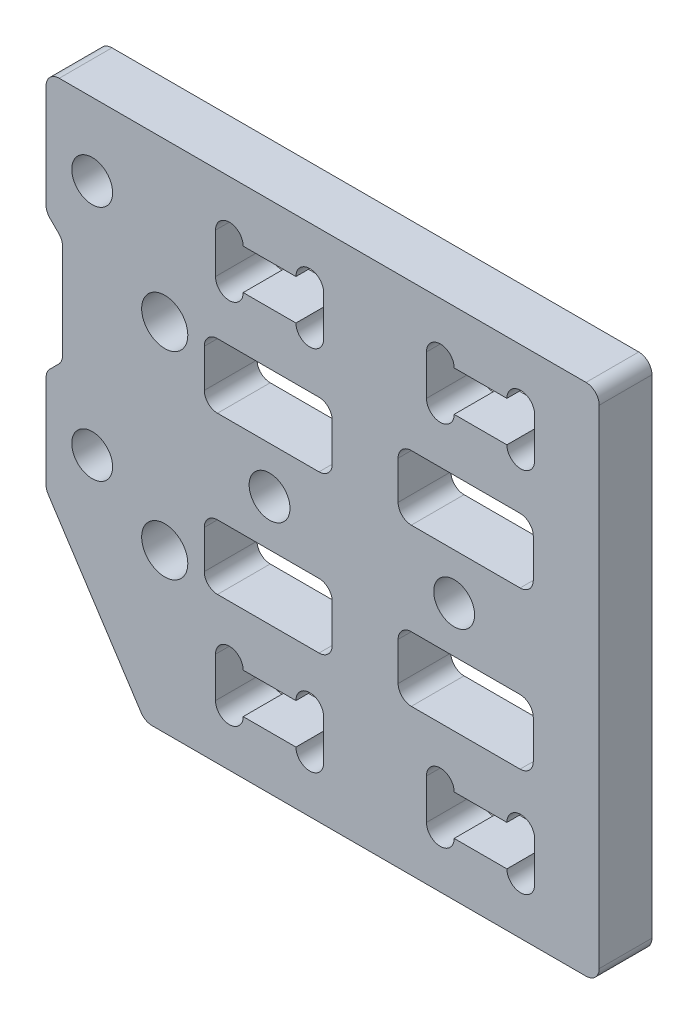
SolidWorks part; units mm, degrees
material "Thornel Mat VMA"
ref_plane "前视基准面" through (0, 0, 0) normal (0, 0, 1) x (1, 0, 0)
ref_plane "上视基准面" through (0, 0, 0) normal (0, 1, 0) x (1, 0, 0)
ref_plane "右视基准面" through (0, 0, 0) normal (1, 0, 0) x (0, 0, -1)
sketch "草图1" plane through (0, 0, 0) normal (0, 0, 1) x (1, 0, 0)
  line L0 (-24.725, 13.925) -> (34.2998, 13.925) construction
  line L1 (17.225, -19.5) -> (-17.225, -19.5)
  line L2 (17.225, -19.5) -> (17.225, 19.5)
  line L3 (17.225, 19.5) -> (-14.225, 19.5)
  line L4 (-17.225, -19.5) -> (-17.225, 19.5) construction
  line L5 (17.225, -19.5) -> (-17.225, 19.5) construction
  line L6 (17.225, 19.5) -> (-17.225, -19.5) construction
  line L7 (0, 0) -> (25.8004, 0) construction
  line L8 (-24.725, -13.925) -> (34.2998, -13.925) construction
  line L9 (-24.725, 19.5) -> (-24.725, 10.25)
  line L10 (-3.675, 12.4) -> (-11.875, 12.4)
  line L11 (-3.675, 12.4) -> (-3.675, 15.45)
  line L12 (-3.675, 15.45) -> (-11.875, 15.45)
  line L13 (-11.875, 12.4) -> (-11.875, 15.45)
  line L14 (-3.675, 12.4) -> (-11.875, 15.45) construction
  line L15 (-3.675, 15.45) -> (-11.875, 12.4) construction
  line L16 (12.325, 12.4) -> (4.125, 12.4)
  line L17 (12.325, 12.4) -> (12.325, 15.45)
  line L18 (12.325, 15.45) -> (4.125, 15.45)
  line L19 (4.125, 12.4) -> (4.125, 15.45)
  line L20 (12.325, 12.4) -> (4.125, 15.45) construction
  line L21 (12.325, 15.45) -> (4.125, 12.4) construction
  line L23 (-21.225, -4) -> (-21.225, 14) construction
  line L24 (4.125, -15.45) -> (12.325, -15.45)
  line L25 (4.125, -15.45) -> (4.125, -12.4)
  line L26 (4.125, -12.4) -> (12.325, -12.4)
  line L27 (12.325, -15.45) -> (12.325, -12.4)
  line L28 (4.125, -15.45) -> (12.325, -12.4) construction
  line L29 (4.125, -12.4) -> (12.325, -15.45) construction
  line L35 (-24.725, -8) -> (-17.225, -19.5)
  line L37 (-21.225, 5) -> (-19.725, 5) construction
  line L42 (-14.225, -1) -> (-19.225, -1) construction
  line L43 (-14.225, -1) -> (-14.225, 11) construction
  line L44 (12.225, -8.4) -> (1.975, -8.4)
  line L45 (12.225, -8.4) -> (12.225, -3.5)
  line L46 (12.225, 8.4) -> (1.975, 8.4)
  line L47 (-12.225, -8.4) -> (-12.225, -3.5) construction
  line L48 (12.225, -8.4) -> (-12.225, 8.4) construction
  line L49 (12.225, 8.4) -> (-12.225, -8.4) construction
  line L50 (-19.725, 21) -> (-19.725, -11) construction
  line L51 (-14.225, 11) -> (-19.225, 11) construction
  line L56 (-3.675, -15.45) -> (-11.875, -15.45)
  line L57 (-11.875, -12.4) -> (-11.875, -15.45)
  line L58 (-3.675, -12.4) -> (-11.875, -12.4)
  line L59 (-3.675, -12.4) -> (-3.675, -15.45)
  line L60 (-19.225, -1) -> (-19.225, 11) construction
  line L69 (-14.225, -1) -> (-19.225, 11) construction
  line L70 (-14.225, 11) -> (-19.225, -1) construction
  line L93 (-10.2, -5) -> (-12.225, -5) construction
  line L102 (0, 0) -> (0, 10.4804) construction
  line L103 (-3.025, 8.4) -> (-12.225, 8.4) construction
  line L104 (-3.025, -8.4) -> (-12.225, -8.4) construction
  line L105 (-3.025, 8.4) -> (-3.025, 3.5)
  line L106 (1.975, 8.4) -> (1.975, 3.5)
  line L107 (-12.225, -5) -> (-12.225, -8.4) construction
  line L108 (-12.225, 8.4) -> (-3.025, 8.4)
  line L110 (-12.225, -8.4) -> (-3.025, -8.4)
  line L111 (-0.025, 5) -> (8.25, 5) construction
  line L114 (-14.225, 19.5) -> (-24.725, 19.5)
  line L115 (-12.225, 3.5) -> (-3.025, 3.5)
  line L116 (-12.225, -3.5) -> (-3.025, -3.5)
  line L117 (1.975, -3.5) -> (12.225, -3.5)
  line L118 (1.975, 3.5) -> (12.225, 3.5)
  line L119 (-12.225, 3.5) -> (-12.225, 8.4) construction
  line L120 (-3.025, -3.5) -> (-3.025, -8.4)
  line L121 (1.975, -3.5) -> (1.975, -8.4)
  line L122 (12.225, 3.5) -> (12.225, 8.4)
  line L123 (-12.225, 8.4) -> (-12.725, 8.4)
  line L124 (-12.725, 8.4) -> (-12.725, 3.5)
  line L125 (-12.725, 3.5) -> (-12.225, 3.5)
  line L126 (-12.225, -3.5) -> (-12.725, -3.5)
  line L127 (-12.725, -3.5) -> (-12.725, -8.4)
  line L128 (-12.725, -8.4) -> (-12.225, -8.4)
  line L129 (-24.725, 10.25) -> (-23.475, 9)
  line L130 (-23.475, 9) -> (-23.475, 1)
  line L131 (-23.475, 1) -> (-24.725, -0.25)
  line L132 (-23.475, 5) -> (-21.9139, 5) construction
  line L133 (-24.725, -0.25) -> (-24.725, -8)
  circle A0 centre (-21.225, 14) radius 1.55
  circle A1 centre (-21.225, -4) radius 1.55
  circle A4 centre (11.275, -12.4) radius 1.05
  circle A5 centre (5.175, -12.4) radius 1.05
  circle A6 centre (5.175, -15.45) radius 1.05
  circle A7 centre (11.275, -15.45) radius 1.05
  circle A8 centre (11.275, 12.4) radius 1.05
  circle A9 centre (11.275, 15.45) radius 1.05
  circle A10 centre (5.175, 15.45) radius 1.05
  circle A11 centre (5.175, 12.4) radius 1.05
  circle A12 centre (-4.725, 15.45) radius 1.05
  circle A13 centre (-4.725, 12.4) radius 1.05
  circle A14 centre (-10.825, 15.45) radius 1.05
  circle A15 centre (-10.825, 12.4) radius 1.05
  circle A20 centre (-10.825, -15.45) radius 1.05
  circle A21 centre (-10.825, -12.4) radius 1.05
  circle A22 centre (-4.725, -12.4) radius 1.05
  circle A23 centre (-4.725, -15.45) radius 1.05
  circle A24 centre (-7.775, 0) radius 1.55
  circle A25 centre (6.225, 0) radius 1.55
  circle A26 centre (-15.725, 7.5) radius 1.75
  circle A27 centre (-15.725, -7.5) radius 1.75
  point P0 (0, 0)
  point P12 (-7.775, 13.925)
  point P17 (8.225, 13.925)
  point P26 (-16.725, 5)
  point P28 (8.225, -13.925)
  dimension "D9" = 3.1
  dimension "D12" = 2.1
  dimension "D22" = 3.1
  dimension "D26" = 8.5
  dimension "D36" = 3.5
  dimension "D27" = 14
  dimension "D28" = 14
  dimension "D1" = 27.85
  dimension "D2" = 16
  dimension "D3" = 8.2
  dimension "D4" = 3.05
  dimension "D5" = 18
  dimension "D6" = 4
  dimension "D7" = 13.45
  dimension "D8" = 9
  dimension "D10" = 5
  dimension "D11" = 4
  dimension "D13" = 39
  dimension "D14" = 3.5
  dimension "D15" = 5
  dimension "D16" = 2
  dimension "D17" = 12
  dimension "D18" = 4
  dimension "D19" = 4
  dimension "D20" = 5
  dimension "D21" = 32
  dimension "D23" = 1.5
  dimension "D24" = 11
  dimension "D25" = 7
  dimension "D29" = 2
  dimension "D30" = 5
  dimension "D31" = 8
  dimension "D32" = 135
  dimension "D33" = 1.25
  dimension "D34" = 15
  dimension "D35" = 21.2
  dimension "D37" = 5.5
extrude "凸台-拉伸1" add sketch "草图1" along normal blind 4
fillet "圆角1" radius 1 25 edges at (1.975, -8.4, 2) (12.225, -8.4, 2) (12.225, -3.5, 2) (1.975, -3.5, 2) (12.225, 8.4, 2) (1.975, 3.5, 2) (12.225, 3.5, 2) (-3.025, -8.4, 2) (-3.025, -3.5, 2) (-12.725, -3.5, 2) (-12.725, -8.4, 2) (1.975, 8.4, 2) (-3.025, 3.5, 2) (-3.025, 8.4, 2) (-12.725, 3.5, 2) (-12.725, 8.4, 2) (17.225, 19.5, 2) (17.225, -19.5, 2) (-17.225, -19.5, 2) (-24.725, 19.5, 2) (-23.475, 1, 2) (-23.475, 9, 2) (-24.725, 10.25, 2) (-24.725, -0.25, 2) (-24.725, -8, 2)
